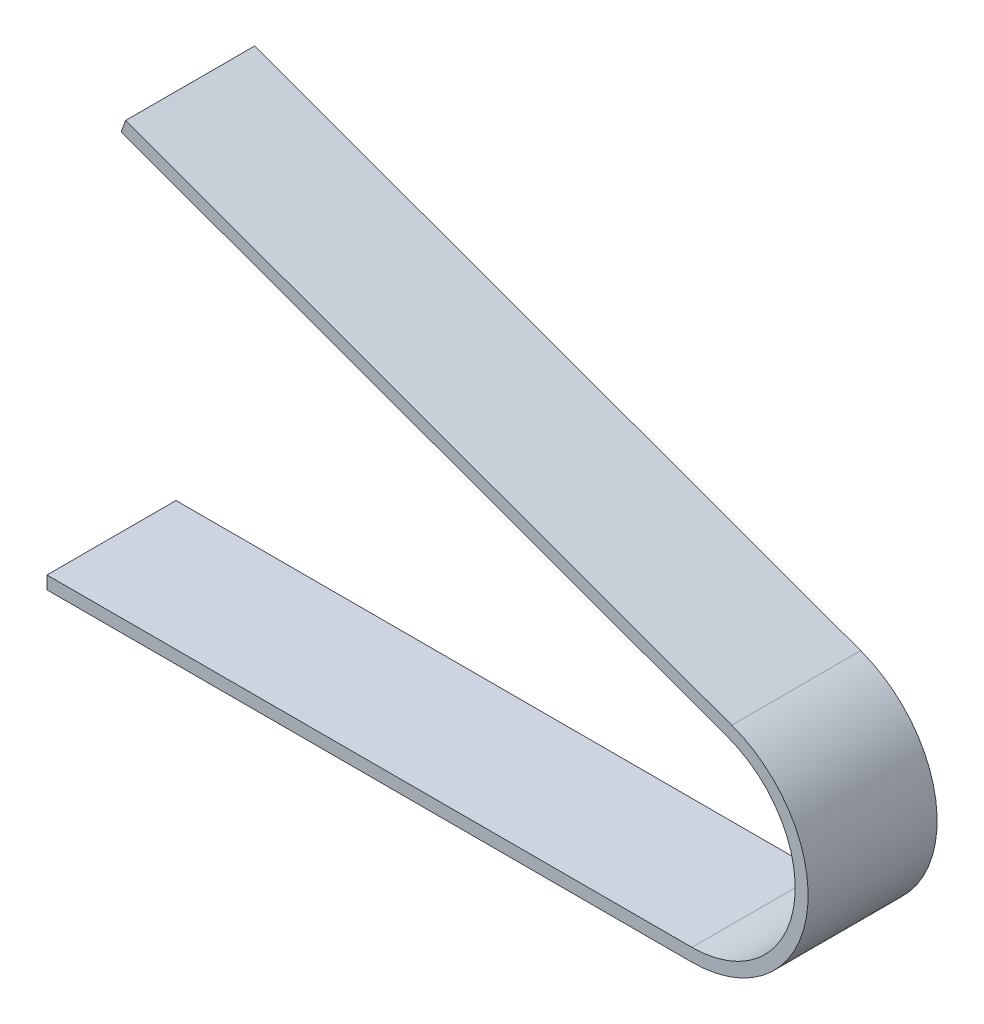
SolidWorks part; units mm, degrees
ref_plane "Front Plane" through (0, 0, 0) normal (0, 0, 1) x (1, 0, 0)
ref_plane "Top Plane" through (0, 0, 0) normal (0, 1, 0) x (1, 0, 0)
ref_plane "Right Plane" through (0, 0, 0) normal (1, 0, 0) x (0, 0, -1)
sketch "Sketch1" plane through (0, 0, 0) normal (0, 0, 1) x (1, 0, 0)
  line L0 (0, -8) -> (-50, -8)
  line L1 (2.7362, 7.5175) -> (-44.2485, 24.6185)
  arc A0 (2.7362, 7.5175) -> (0, -8) centre (0, 0) cw
  dimension "D1" = 8
  dimension "D2" = 20
  dimension "D3" = 50
extrude "Extrude-Thin1" add sketch "Sketch1" along normal blind 10 thin contours L0 A0 L1 thin type one direction wall 1
